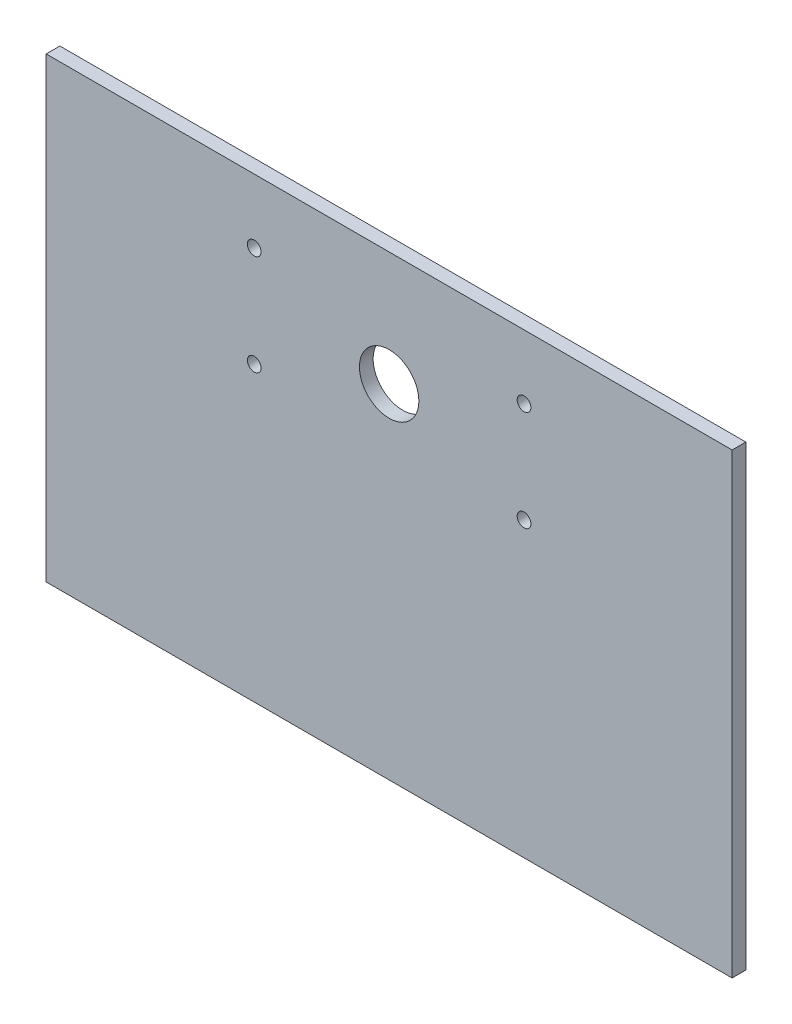
SolidWorks part; units mm, degrees
ref_plane "Plano frontal" through (0, 0, 0) normal (0, 0, 1) x (1, 0, 0)
ref_plane "Plano superior" through (0, 0, 0) normal (0, 1, 0) x (1, 0, 0)
ref_plane "Plano direito" through (0, 0, 0) normal (1, 0, 0) x (0, 0, -1)
sketch "Esboço1" plane through (0, 0, 0) normal (0, 0, 1) x (1, 0, 0)
  line L1 (0, 100) -> (150, 100)
  line L2 (0, 100) -> (0, 0)
  line L3 (0, 0) -> (150, 0)
  line L4 (150, 100) -> (150, 0)
  circle A0 centre (75, 75) radius 6.5
  circle A1 centre (104.5, 86) radius 1.5
  circle A2 centre (104.5, 64) radius 1.5
  circle A3 centre (45.5, 64) radius 1.5
  circle A4 centre (45.5, 86) radius 1.5
  point P4 (75, 100)
  dimension "D4" = 13
  dimension "D3" = 25
  dimension "D7" = 3
  dimension "D8" = 75
  dimension "D12" = 3
  dimension "D13" = 3
  dimension "D14" = 3
  dimension "D1" = 150
  dimension "D2" = 100
  dimension "D5" = 22
  dimension "D6" = 59
  dimension "D9" = 45.5
  dimension "D10" = 22
extrude "Ressalto-extrusão1" add sketch "Esboço1" along normal blind 3
